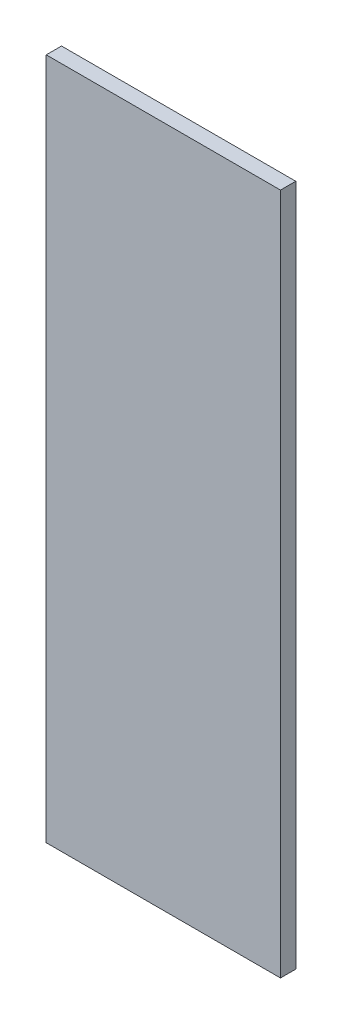
SolidWorks part; units mm, degrees
material "Chapa F.F 1020 - 1,5 mm"
ref_plane "Plano frontal" through (0, 0, 0) normal (0, 0, 1) x (1, 0, 0)
ref_plane "Plano superior" through (0, 0, 0) normal (0, 1, 0) x (1, 0, 0)
ref_plane "Plano direito" through (0, 0, 0) normal (1, 0, 0) x (0, 0, -1)
sketch "Esboço1" plane through (0, 0, 0) normal (0, 0, 1) x (1, 0, 0)
  line L1 (-11.5, -33.5) -> (11.5, -33.5)
  line L2 (-11.5, -33.5) -> (-11.5, 33.5)
  line L3 (-11.5, 33.5) -> (11.5, 33.5)
  line L4 (11.5, -33.5) -> (11.5, 33.5)
  line L5 (-11.5, -33.5) -> (11.5, 33.5) construction
  line L6 (-11.5, 33.5) -> (11.5, -33.5) construction
  point P0 (0, 0)
  dimension "D1" = 67
  dimension "D2" = 23
extrude "Ressalto-extrusão1" add sketch "Esboço1" along normal blind 1.5
